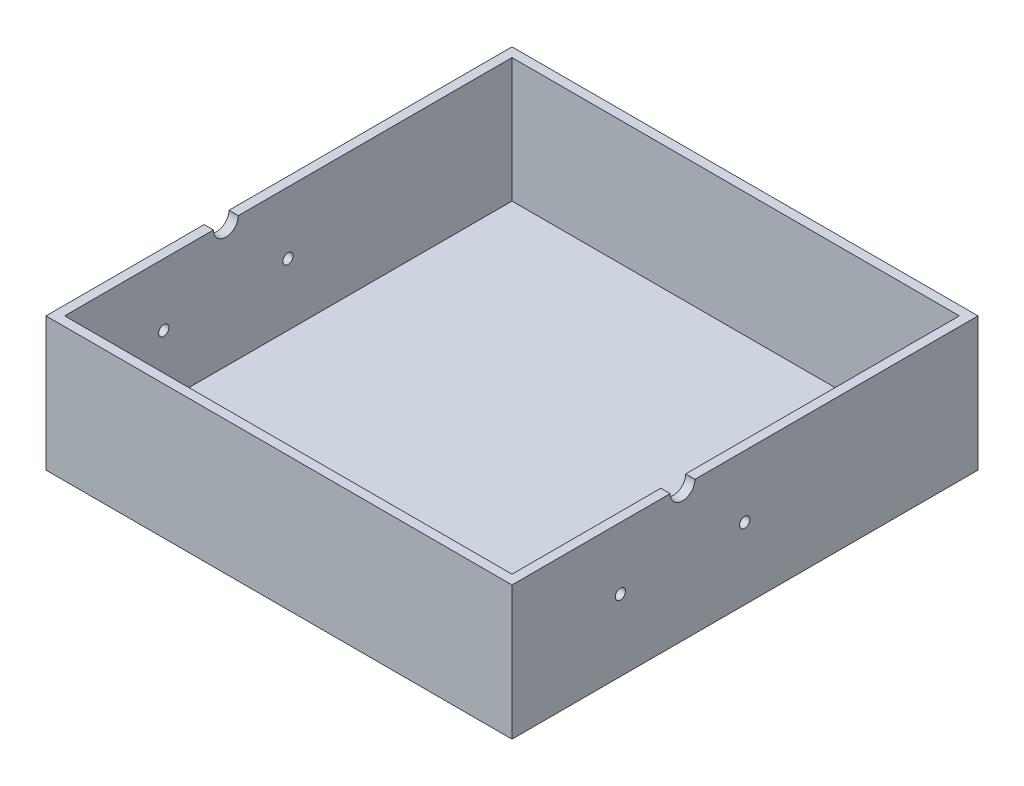
SolidWorks part; units mm, degrees
ref_plane "前视基准面" through (0, 0, 0) normal (0, 0, 1) x (1, 0, 0)
ref_plane "上视基准面" through (0, 0, 0) normal (0, 1, 0) x (1, 0, 0)
ref_plane "右视基准面" through (0, 0, 0) normal (1, 0, 0) x (0, 0, -1)
sketch "草图1" plane through (0, 0, 0) normal (0, 1, 0) x (1, 0, 0)
  line L1 (-75, -75) -> (75, -75)
  line L2 (-75, -75) -> (-75, 75)
  line L3 (-75, 75) -> (75, 75)
  line L4 (75, -75) -> (75, 75)
  line L5 (-75, -75) -> (75, 75) construction
  line L6 (-75, 75) -> (75, -75) construction
  point P0 (0, 0)
  dimension "D1" = 150
  dimension "D2" = 150
extrude "凸台-拉伸1" add sketch "草图1" along normal blind 3
sketch "草图2" plane through (0, 3, 0) normal (0, 1, 0) x (1, 0, 0)
  line L1 (75, -75) -> (-75, -75)
  line L2 (75, -75) -> (75, 75)
  line L3 (75, 75) -> (-75, 75)
  line L4 (-75, -75) -> (-75, 75)
  line L5 (75, -75) -> (-75, 75) construction
  line L6 (75, 75) -> (-75, -75) construction
  line L7 (72, -72) -> (-72, -72)
  line L8 (72, -72) -> (72, 72)
  line L9 (72, 72) -> (-72, 72)
  line L10 (-72, -72) -> (-72, 72)
  line L11 (72, -72) -> (-72, 72) construction
  line L12 (72, 72) -> (-72, -72) construction
  point P1 (0, 0)
  point P7 (0, 0)
  dimension "D1" = 144
extrude "凸台-拉伸2" add sketch "草图2" along normal blind 40
sketch "草图3" plane through (75, 0, 0) normal (1, 0, 0) x (0, 0, -1)
  line L0 (-75, 43) -> (75, 43) construction
  line L1 (-75, 43) -> (-75, 0) construction
  line L2 (-20.1, 39) -> (-20.1, 19.8129) construction
  circle A0 centre (-20.1, 43) radius 4
  circle A1 centre (-0.1, 23) radius 1.65
  circle A2 centre (-40.1, 23) radius 1.65
  point P12 (0, 0)
  dimension "D2" = 8
  dimension "D3" = 3.3
  dimension "D4" = 3.3
  dimension "D1" = 54.9
  dimension "D5" = 40
  dimension "D6" = 20
extrude "切除-拉伸1" cut sketch "草图3" against normal through all
